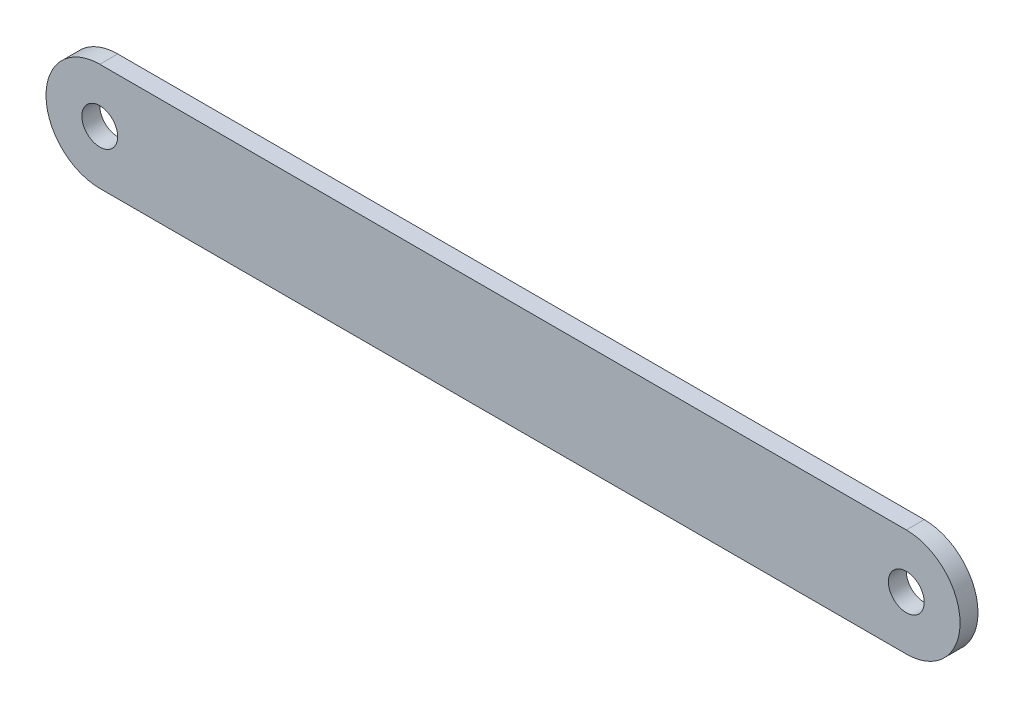
SolidWorks part; units mm, degrees
ref_plane "Front Plane" through (0, 0, 0) normal (0, 0, 1) x (1, 0, 0)
ref_plane "Top Plane" through (0, 0, 0) normal (0, 1, 0) x (1, 0, 0)
ref_plane "Right Plane" through (0, 0, 0) normal (1, 0, 0) x (0, 0, -1)
sketch "Sketch1" plane through (0, 0, 0) normal (0, 0, 1) x (1, 0, 0)
  line L0 (-450, 0) -> (450, 0) construction
  line L1 (-450, 60) -> (450, 60)
  line L2 (-450, -60) -> (450, -60)
  arc A0 (-450, 60) -> (-450, -60) centre (-450, 0) ccw
  arc A1 (450, -60) -> (450, 60) centre (450, 0) ccw
  circle A2 centre (450, 0) radius 20
  circle A3 centre (-450, 0) radius 20
  point P3 (0, 0)
  dimension "D3" = 60
  dimension "D4" = 40
  dimension "D5" = 40
  dimension "D1" = 900
  dimension "D2" = 450
extrude "Boss-Extrude1" add sketch "Sketch1" along normal blind 20
